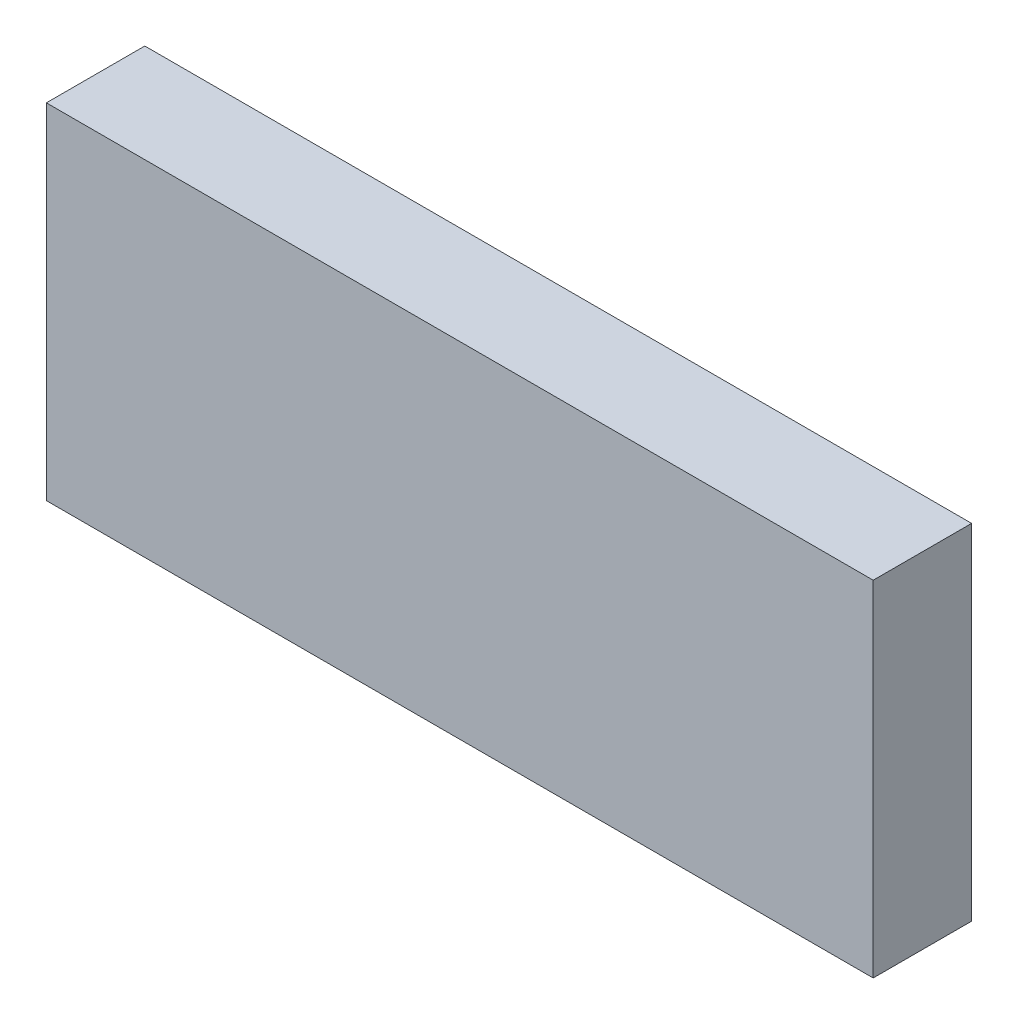
SolidWorks part; units mm, degrees
ref_plane "Front Plane" through (0, 0, 0) normal (0, 0, 1) x (1, 0, 0)
ref_plane "Top Plane" through (0, 0, 0) normal (0, 1, 0) x (1, 0, 0)
ref_plane "Right Plane" through (0, 0, 0) normal (1, 0, 0) x (0, 0, -1)
sketch "Sketch1" plane through (0, 0, 0) normal (0, 0, 1) x (1, 0, 0)
  line L1 (-53.34, -22.225) -> (53.34, -22.225)
  line L2 (-53.34, -22.225) -> (-53.34, 22.225)
  line L3 (-53.34, 22.225) -> (53.34, 22.225)
  line L4 (53.34, -22.225) -> (53.34, 22.225)
  line L5 (-53.34, -22.225) -> (53.34, 22.225) construction
  line L6 (-53.34, 22.225) -> (53.34, -22.225) construction
  point P0 (0, 0)
  dimension "D1" = 44.45
  dimension "D2" = 106.68
extrude "Boss-Extrude1" add sketch "Sketch1" along normal blind 12.7
